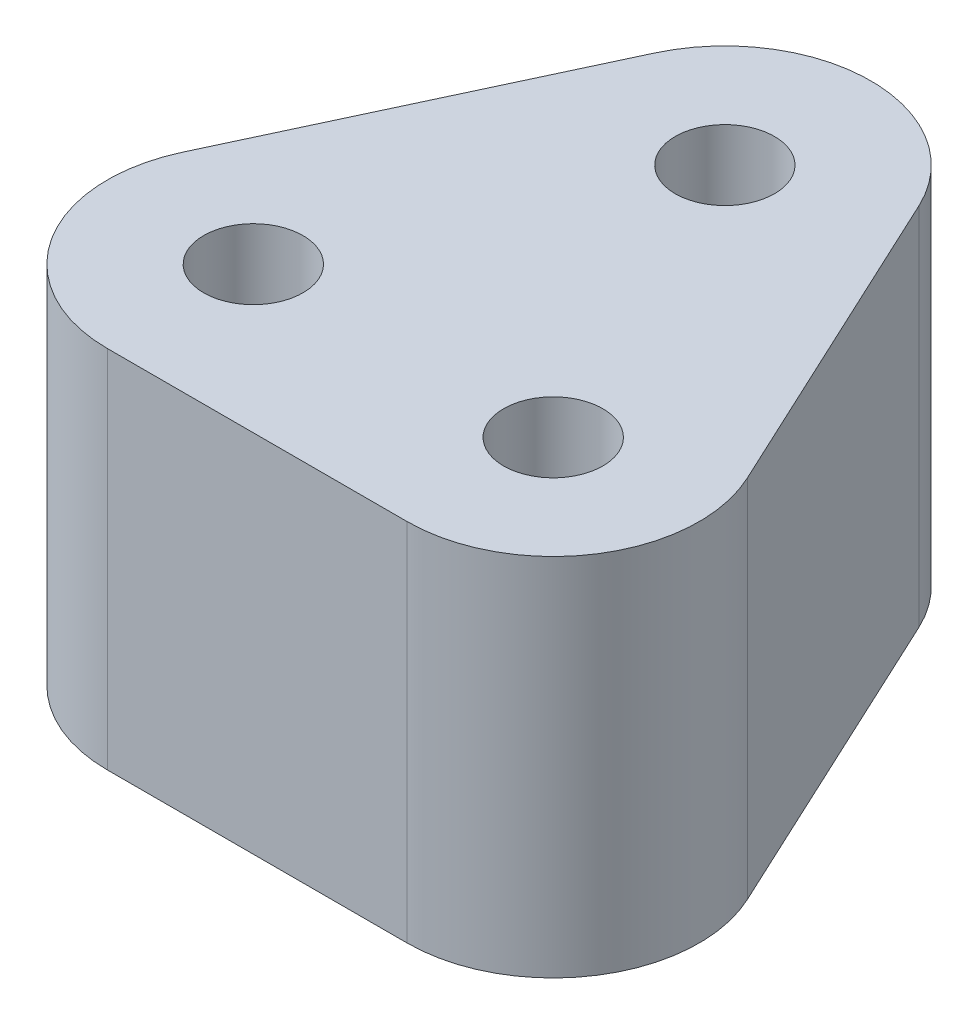
SolidWorks part; units mm, degrees
material "POM 乙缩醛共聚物"
ref_plane "前视基准面" through (0, 0, 0) normal (0, 0, 1) x (1, 0, 0)
ref_plane "上视基准面" through (0, 0, 0) normal (0, 1, 0) x (1, 0, 0)
ref_plane "右视基准面" through (0, 0, 0) normal (1, 0, 0) x (0, 0, -1)
sketch "草图1" plane through (0, 0, 0) normal (0, 1, 0) x (1, 0, 0)
  line L0 (-12.9839, -16.0131) -> (-4.5315, 2.1131)
  line L1 (12.9839, -16.0131) -> (4.5315, 2.1131)
  line L2 (0, 0) -> (0, 11.1129) construction
  line L3 (-12.9839, -16.0131) -> (12.9839, -16.0131)
  circle A0 centre (0, 0) radius 1.7
  arc A1 (4.5315, 2.1131) -> (-4.5315, 2.1131) centre (0, 0) ccw
  dimension "D1" = 3.4
  dimension "D2" = 10
  dimension "D3" = 25
  dimension "D4" = 25
  dimension "D5" = 20
  dimension "D6" = 20
extrude "凸台-拉伸1" add sketch "草图1" along normal blind 12.5
fillet "圆角1" radius 5 2 edges at (-12.9839, 6.25, 16.0131) (12.9839, 6.25, 16.0131)
sketch "草图2" plane through (0, 12.5, 0) normal (0, 1, 0) x (1, 0, 0)
  circle A0 centre (-5.1355, -11.0131) radius 1.7
  circle A1 centre (5.1355, -11.0131) radius 1.7
  dimension "D1" = 3.4
  dimension "D2" = 3.4
extrude "切除-拉伸1" cut sketch "草图2" against normal blind 14
